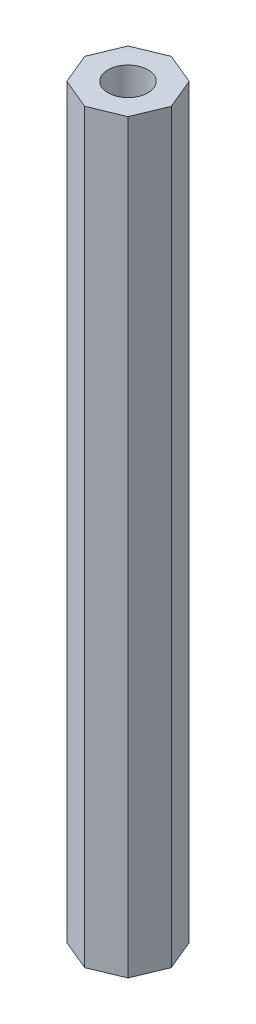
SolidWorks part; units mm, degrees
ref_plane "Front" through (0, 0, 0) normal (0, 0, 1) x (1, 0, 0)
ref_plane "Top" through (0, 0, 0) normal (0, 1, 0) x (1, 0, 0)
ref_plane "Right" through (0, 0, 0) normal (1, 0, 0) x (0, 0, -1)
sketch "Sketch1" plane through (0, 0, 0) normal (0, 1, 0) x (1, 0, 0)
  line L1 (1.6236, 0) -> (1.1481, 1.1481)
  line L2 (1.1481, 1.1481) -> (0, 1.6236)
  line L3 (0, 1.6236) -> (-1.1481, 1.1481)
  line L4 (-1.1481, 1.1481) -> (-1.6236, 0)
  line L5 (-1.6236, 0) -> (-1.1481, -1.1481)
  line L6 (-1.1481, -1.1481) -> (0, -1.6236)
  line L7 (0, -1.6236) -> (1.1481, -1.1481)
  line L8 (1.1481, -1.1481) -> (1.6236, 0)
  circle A0 centre (0, 0) radius 1.5 construction
  circle A1 centre (0, 0) radius 0.75
extrude "Boss-Extrude1" add sketch "Sketch1" along normal blind 28
